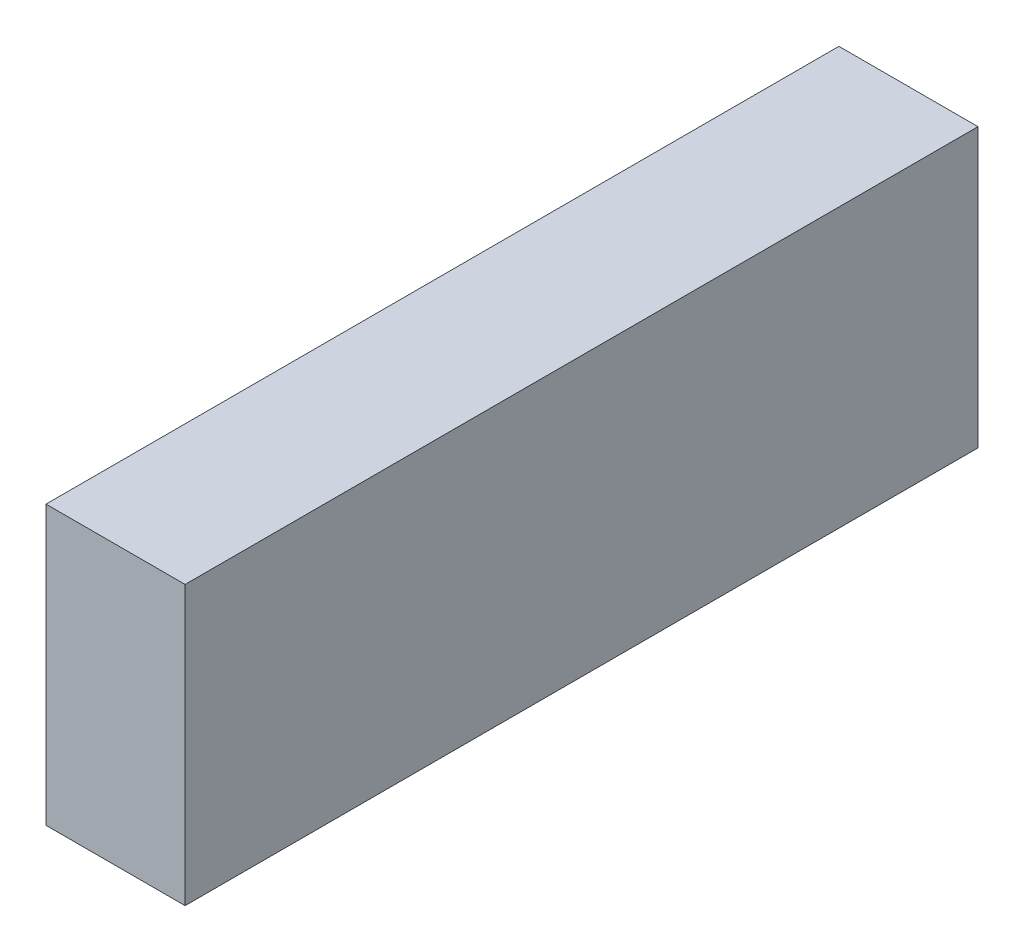
SolidWorks part; units mm, degrees
ref_plane "Front Plane" through (0, 0, 0) normal (0, 0, 1) x (1, 0, 0)
ref_plane "Top Plane" through (0, 0, 0) normal (0, 1, 0) x (1, 0, 0)
ref_plane "Right Plane" through (0, 0, 0) normal (1, 0, 0) x (0, 0, -1)
sketch "Sketch1" plane through (0, 0, 0) normal (1, 0, 0) x (0, 0, -1)
  line L1 (0, 0) -> (57, 0)
  line L2 (0, 0) -> (0, 20)
  line L3 (0, 20) -> (57, 20)
  line L4 (57, 0) -> (57, 20)
extrude "Boss-Extrude1" add sketch "Sketch1" against normal blind 10
